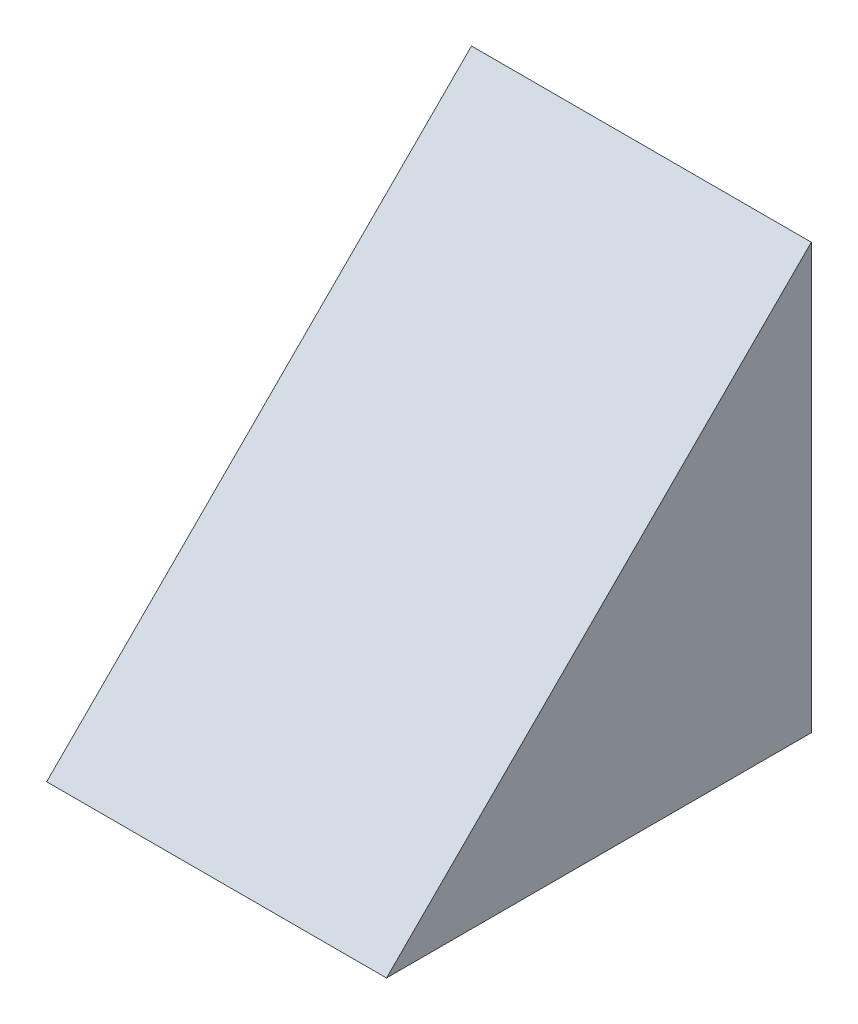
SolidWorks part; units mm, degrees
ref_plane "Front Plane" through (0, 0, 0) normal (0, 0, 1) x (1, 0, 0)
ref_plane "Top Plane" through (0, 0, 0) normal (0, 1, 0) x (1, 0, 0)
ref_plane "Right Plane" through (0, 0, 0) normal (1, 0, 0) x (0, 0, -1)
sketch "Sketch2" plane through (0, 0, 0) normal (1, 0, 0) x (0, 0, -1)
  line L0 (-12.5, 0) -> (12.5, 0)
  line L1 (12.5, 0) -> (12.5, 25)
  line L2 (12.5, 25) -> (-12.5, 0)
  dimension "D1" = 25
  dimension "D2" = 25
extrude "Boss-Extrude1" add sketch "Sketch2" along normal blind 20
sketch "Sketch3" plane through (0, 0, -12.5) normal (0, 0, -1) x (-1, 0, 0)
  line L0 (-20, 0) -> (0, 0) construction
  line L1 (-20, 0) -> (-20, 25) construction
  circle A0 centre (-10, 10) radius 2
  dimension "D1" = 4
  dimension "D2" = 10
  dimension "D3" = 10
extrude "Cut-Extrude1" cut sketch "Sketch3" against normal blind 6
sketch "Sketch4" plane through (0, 0, 0) normal (0, -1, 0) x (1, 0, 0)
  line L0 (0, 12.5) -> (0, -12.5) construction
  line L1 (20, -12.5) -> (0, -12.5) construction
  circle A0 centre (10, -2.5) radius 2
  dimension "D1" = 4
  dimension "D2" = 10
  dimension "D3" = 10
extrude "Cut-Extrude2" cut sketch "Sketch4" against normal blind 6
